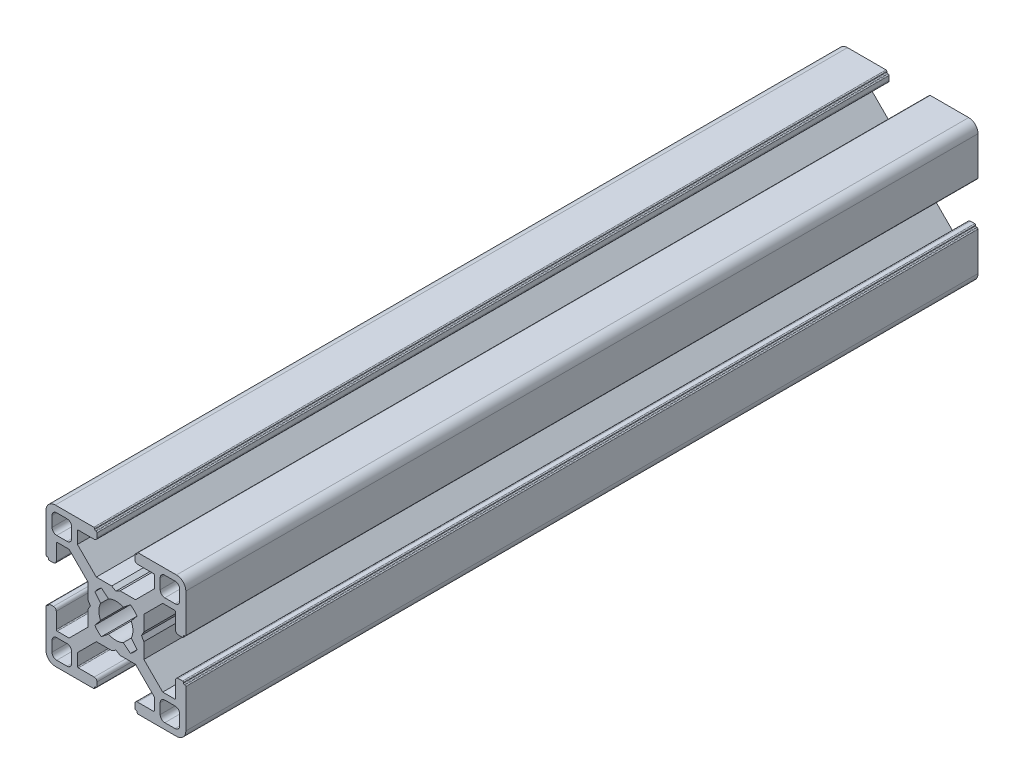
SolidWorks part; units mm, degrees
material "6063 Aluminum Alloy"
ref_plane "Płaszczyzna przednia" through (0, 0, 0) normal (0, 0, 1) x (1, 0, 0)
ref_plane "Płaszczyzna górna" through (0, 0, 0) normal (0, 1, 0) x (1, 0, 0)
ref_plane "Płaszczyzna prawa" through (0, 0, 0) normal (1, 0, 0) x (0, 0, -1)
sketch "Szkic1" plane through (0, 0, 0) normal (0, 0, 1) x (1, 0, 0)
  line L0 (12.7, 13.7) -> (10.5, 13.7)
  line L1 (9.5, 12.7) -> (9.5, 10.5)
  line L2 (10.5, 9.5) -> (12.7, 9.5)
  line L3 (13.7, 10.5) -> (13.7, 12.7)
  line L4 (-1.5829, 3.2889) -> (-3.1172, 4.5314)
  line L5 (-4.5314, 3.1172) -> (-3.2889, 1.5829)
  line L6 (-3.2889, -1.5829) -> (-4.5314, -3.1172)
  line L7 (-3.1172, -4.5314) -> (-1.5829, -3.2889)
  line L8 (1.5829, -3.2889) -> (3.1172, -4.5314)
  line L9 (4.5314, -3.1172) -> (3.2889, -1.5829)
  line L10 (3.2889, 1.5829) -> (4.5314, 3.1172)
  line L11 (3.1172, 4.5314) -> (1.5829, 3.2889)
  line L12 (-12.7, -13.7) -> (-10.5, -13.7)
  line L13 (-9.5, -12.7) -> (-9.5, -10.5)
  line L14 (-10.5, -9.5) -> (-12.7, -9.5)
  line L15 (-13.7, -10.5) -> (-13.7, -12.7)
  line L16 (13.7, -12.7) -> (13.7, -10.5)
  line L17 (12.7, -9.5) -> (10.5, -9.5)
  line L18 (9.5, -10.5) -> (9.5, -12.7)
  line L19 (-10.5, 13.7) -> (-12.7, 13.7)
  line L20 (-13.7, 12.7) -> (-13.7, 10.5)
  line L21 (-12.7, 9.5) -> (-10.5, 9.5)
  line L22 (-9.5, 10.5) -> (-9.5, 12.7)
  line L23 (10.5, -13.7) -> (12.7, -13.7)
  line L24 (0, -5.48) -> (0.9007, -6)
  line L25 (0.9007, -6) -> (4.2039, -6)
  line L26 (4.2039, -6) -> (8.25, -10.0461)
  line L27 (8.25, -10.0461) -> (8.25, -12.6)
  line L28 (8.05, -12.8) -> (4.65, -12.8)
  line L29 (4.05, -13.4) -> (4.05, -14.3)
  line L30 (4.25, -14.5) -> (4.35, -14.5)
  line L31 (4.55, -14.7) -> (4.55, -14.8)
  line L32 (4.75, -15) -> (13, -15)
  line L33 (15, -13) -> (15, -4.75)
  line L34 (14.8, -4.55) -> (14.7, -4.55)
  line L35 (14.5, -4.35) -> (14.5, -4.25)
  line L36 (14.3, -4.05) -> (13.4, -4.05)
  line L37 (12.8, -4.65) -> (12.8, -8.05)
  line L38 (12.6, -8.25) -> (10.0461, -8.25)
  line L39 (10.0461, -8.25) -> (6, -4.2039)
  line L40 (6, -4.2039) -> (6, -0.9007)
  line L41 (6, -0.9007) -> (5.48, 0)
  line L42 (5.48, 0) -> (6, 0.9007)
  line L43 (6, 0.9007) -> (6, 4.2039)
  line L44 (6, 4.2039) -> (10.0461, 8.25)
  line L45 (10.0461, 8.25) -> (12.6, 8.25)
  line L46 (12.8, 8.05) -> (12.8, 4.65)
  line L47 (13.4, 4.05) -> (14.3, 4.05)
  line L48 (14.5, 4.25) -> (14.5, 4.35)
  line L49 (14.7, 4.55) -> (14.8, 4.55)
  line L50 (15, 4.75) -> (15, 13)
  line L51 (13, 15) -> (4.75, 15)
  line L52 (4.55, 14.8) -> (4.55, 14.7)
  line L53 (4.35, 14.5) -> (4.25, 14.5)
  line L54 (4.05, 14.3) -> (4.05, 13.4)
  line L55 (4.65, 12.8) -> (8.05, 12.8)
  line L56 (8.25, 12.6) -> (8.25, 10.0461)
  line L57 (8.25, 10.0461) -> (4.2039, 6)
  line L58 (4.2039, 6) -> (0.9007, 6)
  line L59 (0.9007, 6) -> (0, 5.48)
  line L60 (0, 5.48) -> (-0.9007, 6)
  line L61 (-0.9007, 6) -> (-4.2039, 6)
  line L62 (-4.2039, 6) -> (-8.25, 10.0461)
  line L63 (-8.25, 10.0461) -> (-8.25, 12.6)
  line L64 (-8.05, 12.8) -> (-4.65, 12.8)
  line L65 (-4.05, 13.4) -> (-4.05, 14.3)
  line L66 (-4.25, 14.5) -> (-4.35, 14.5)
  line L67 (-4.55, 14.7) -> (-4.55, 14.8)
  line L68 (-4.75, 15) -> (-13, 15)
  line L69 (-15, 13) -> (-15, 4.75)
  line L70 (-14.8, 4.55) -> (-14.7, 4.55)
  line L71 (-14.5, 4.35) -> (-14.5, 4.25)
  line L72 (-14.3, 4.05) -> (-13.4, 4.05)
  line L73 (-12.8, 4.65) -> (-12.8, 8.05)
  line L74 (-12.6, 8.25) -> (-10.0461, 8.25)
  line L75 (-10.0461, 8.25) -> (-6, 4.2039)
  line L76 (-6, 4.2039) -> (-6, 0.9007)
  line L77 (-6, 0.9007) -> (-5.48, 0)
  line L78 (-5.48, 0) -> (-6, -0.9007)
  line L79 (-6, -0.9007) -> (-6, -4.2039)
  line L80 (-6, -4.2039) -> (-10.0461, -8.25)
  line L81 (-10.0461, -8.25) -> (-12.6, -8.25)
  line L82 (-12.8, -8.05) -> (-12.8, -4.65)
  line L83 (-13.4, -4.05) -> (-14.3, -4.05)
  line L84 (-14.5, -4.25) -> (-14.5, -4.35)
  line L85 (-14.7, -4.55) -> (-14.8, -4.55)
  line L86 (-15, -4.75) -> (-15, -13)
  line L87 (-13, -15) -> (-4.75, -15)
  line L88 (-4.55, -14.8) -> (-4.55, -14.7)
  line L89 (-4.35, -14.5) -> (-4.25, -14.5)
  line L90 (-4.05, -14.3) -> (-4.05, -13.4)
  line L91 (-4.65, -12.8) -> (-8.05, -12.8)
  line L92 (-8.25, -12.6) -> (-8.25, -10.0461)
  line L93 (-8.25, -10.0461) -> (-4.2039, -6)
  line L94 (-4.2039, -6) -> (-0.9007, -6)
  line L95 (-0.9007, -6) -> (0, -5.48)
  line L96 (-3.8891, -3.8891) -> (3.8891, 3.8891) construction
  line L97 (-3.8891, 3.8891) -> (3.8891, -3.8891) construction
  line L98 (55, 0) -> (-55, 0) construction
  arc A0 (10.5, 13.7) -> (9.5, 12.7) centre (10.5, 12.7) ccw
  arc A1 (9.5, 10.5) -> (10.5, 9.5) centre (10.5, 10.5) ccw
  arc A2 (12.7, 9.5) -> (13.7, 10.5) centre (12.7, 10.5) ccw
  arc A3 (13.7, 12.7) -> (12.7, 13.7) centre (12.7, 12.7) ccw
  arc A4 (-3.1172, 4.5314) -> (-4.5314, 3.1172) centre (0, 0) ccw
  arc A5 (-3.2889, 1.5829) -> (-3.2889, -1.5829) centre (0, 0) ccw
  arc A6 (-4.5314, -3.1172) -> (-3.1172, -4.5314) centre (0, 0) ccw
  arc A7 (-1.5829, -3.2889) -> (1.5829, -3.2889) centre (0, 0) ccw
  arc A8 (3.1172, -4.5314) -> (4.5314, -3.1172) centre (0, 0) ccw
  arc A9 (3.2889, -1.5829) -> (3.2889, 1.5829) centre (0, 0) ccw
  arc A10 (4.5314, 3.1172) -> (3.1172, 4.5314) centre (0, 0) ccw
  arc A11 (1.5829, 3.2889) -> (-1.5829, 3.2889) centre (0, 0) ccw
  arc A12 (-10.5, -13.7) -> (-9.5, -12.7) centre (-10.5, -12.7) ccw
  arc A13 (-9.5, -10.5) -> (-10.5, -9.5) centre (-10.5, -10.5) ccw
  arc A14 (-12.7, -9.5) -> (-13.7, -10.5) centre (-12.7, -10.5) ccw
  arc A15 (-13.7, -12.7) -> (-12.7, -13.7) centre (-12.7, -12.7) ccw
  arc A16 (12.7, -13.7) -> (13.7, -12.7) centre (12.7, -12.7) ccw
  arc A17 (13.7, -10.5) -> (12.7, -9.5) centre (12.7, -10.5) ccw
  arc A18 (10.5, -9.5) -> (9.5, -10.5) centre (10.5, -10.5) ccw
  arc A19 (9.5, -12.7) -> (10.5, -13.7) centre (10.5, -12.7) ccw
  arc A20 (-12.7, 13.7) -> (-13.7, 12.7) centre (-12.7, 12.7) ccw
  arc A21 (-13.7, 10.5) -> (-12.7, 9.5) centre (-12.7, 10.5) ccw
  arc A22 (-10.5, 9.5) -> (-9.5, 10.5) centre (-10.5, 10.5) ccw
  arc A23 (-9.5, 12.7) -> (-10.5, 13.7) centre (-10.5, 12.7) ccw
  arc A24 (8.05, -12.8) -> (8.25, -12.6) centre (8.05, -12.6) ccw
  arc A25 (4.65, -12.8) -> (4.05, -13.4) centre (4.65, -13.4) ccw
  arc A26 (4.05, -14.3) -> (4.25, -14.5) centre (4.25, -14.3) ccw
  arc A27 (4.55, -14.7) -> (4.35, -14.5) centre (4.35, -14.7) ccw
  arc A28 (4.55, -14.8) -> (4.75, -15) centre (4.75, -14.8) ccw
  arc A29 (13, -15) -> (15, -13) centre (13, -13) ccw
  arc A30 (15, -4.75) -> (14.8, -4.55) centre (14.8, -4.75) ccw
  arc A31 (14.5, -4.35) -> (14.7, -4.55) centre (14.7, -4.35) ccw
  arc A32 (14.5, -4.25) -> (14.3, -4.05) centre (14.3, -4.25) ccw
  arc A33 (13.4, -4.05) -> (12.8, -4.65) centre (13.4, -4.65) ccw
  arc A34 (12.6, -8.25) -> (12.8, -8.05) centre (12.6, -8.05) ccw
  arc A35 (12.8, 8.05) -> (12.6, 8.25) centre (12.6, 8.05) ccw
  arc A36 (12.8, 4.65) -> (13.4, 4.05) centre (13.4, 4.65) ccw
  arc A37 (14.3, 4.05) -> (14.5, 4.25) centre (14.3, 4.25) ccw
  arc A38 (14.7, 4.55) -> (14.5, 4.35) centre (14.7, 4.35) ccw
  arc A39 (14.8, 4.55) -> (15, 4.75) centre (14.8, 4.75) ccw
  arc A40 (15, 13) -> (13, 15) centre (13, 13) ccw
  arc A41 (4.75, 15) -> (4.55, 14.8) centre (4.75, 14.8) ccw
  arc A42 (4.35, 14.5) -> (4.55, 14.7) centre (4.35, 14.7) ccw
  arc A43 (4.25, 14.5) -> (4.05, 14.3) centre (4.25, 14.3) ccw
  arc A44 (4.05, 13.4) -> (4.65, 12.8) centre (4.65, 13.4) ccw
  arc A45 (8.25, 12.6) -> (8.05, 12.8) centre (8.05, 12.6) ccw
  arc A46 (-8.05, 12.8) -> (-8.25, 12.6) centre (-8.05, 12.6) ccw
  arc A47 (-4.65, 12.8) -> (-4.05, 13.4) centre (-4.65, 13.4) ccw
  arc A48 (-4.05, 14.3) -> (-4.25, 14.5) centre (-4.25, 14.3) ccw
  arc A49 (-4.55, 14.7) -> (-4.35, 14.5) centre (-4.35, 14.7) ccw
  arc A50 (-4.55, 14.8) -> (-4.75, 15) centre (-4.75, 14.8) ccw
  arc A51 (-13, 15) -> (-15, 13) centre (-13, 13) ccw
  arc A52 (-15, 4.75) -> (-14.8, 4.55) centre (-14.8, 4.75) ccw
  arc A53 (-14.5, 4.35) -> (-14.7, 4.55) centre (-14.7, 4.35) ccw
  arc A54 (-14.5, 4.25) -> (-14.3, 4.05) centre (-14.3, 4.25) ccw
  arc A55 (-13.4, 4.05) -> (-12.8, 4.65) centre (-13.4, 4.65) ccw
  arc A56 (-12.6, 8.25) -> (-12.8, 8.05) centre (-12.6, 8.05) ccw
  arc A57 (-12.8, -8.05) -> (-12.6, -8.25) centre (-12.6, -8.05) ccw
  arc A58 (-12.8, -4.65) -> (-13.4, -4.05) centre (-13.4, -4.65) ccw
  arc A59 (-14.3, -4.05) -> (-14.5, -4.25) centre (-14.3, -4.25) ccw
  arc A60 (-14.7, -4.55) -> (-14.5, -4.35) centre (-14.7, -4.35) ccw
  arc A61 (-14.8, -4.55) -> (-15, -4.75) centre (-14.8, -4.75) ccw
  arc A62 (-15, -13) -> (-13, -15) centre (-13, -13) ccw
  arc A63 (-4.75, -15) -> (-4.55, -14.8) centre (-4.75, -14.8) ccw
  arc A64 (-4.35, -14.5) -> (-4.55, -14.7) centre (-4.35, -14.7) ccw
  arc A65 (-4.25, -14.5) -> (-4.05, -14.3) centre (-4.25, -14.3) ccw
  arc A66 (-4.05, -13.4) -> (-4.65, -12.8) centre (-4.65, -13.4) ccw
  arc A67 (-8.25, -12.6) -> (-8.05, -12.8) centre (-8.05, -12.6) ccw
  dimension "D1" = 3.65
  dimension "D7" = 2
  dimension "D9" = 3.65
  dimension "D10" = 5.5
  dimension "D23" = 1
  dimension "D37" = 0.2
  dimension "D59" = 0.6
  dimension "D60" = 0.2
  dimension "D63" = 0.2
  dimension "D64" = 0.2
  dimension "D67" = 0.2
  dimension "D68" = 0.2
  dimension "D69" = 0.2
  dimension "D73" = 0.2
  dimension "D75" = 0.2
  dimension "D76" = 0.2
  dimension "D2" = 30
  dimension "D3" = 30
  dimension "D4" = 8.1
  dimension "D5" = 15
  dimension "D6" = 15
  dimension "D8" = 4.05
  dimension "D11" = 45
  dimension "D12" = 6
  dimension "D13" = 2
  dimension "D14" = 12
  dimension "D15" = 6
  dimension "D16" = 12
  dimension "D17" = 6
  dimension "D18" = 12
  dimension "D19" = 6
  dimension "D20" = 12
  dimension "D21" = 1.3
  dimension "D22" = 1.3
  dimension "D24" = 1.3
  dimension "D25" = 4.2
  dimension "D26" = 4.2
  dimension "D27" = 4.2
  dimension "D28" = 1.3
  dimension "D29" = 4.2
  dimension "D30" = 16.5
  dimension "D31" = 8.25
  dimension "D32" = 2.54
  dimension "D33" = 1.27
  dimension "D34" = 2.54
  dimension "D35" = 1.27
  dimension "D36" = 2.2
  dimension "D38" = 2.2
  dimension "D39" = 2.2
  dimension "D40" = 6
  dimension "D41" = 6
  dimension "D42" = 12
  dimension "D43" = 2
  dimension "D44" = 2
  dimension "D45" = 2
  dimension "D46" = 2.2
  dimension "D47" = 16.5
  dimension "D48" = 8.25
  dimension "D49" = 6
  dimension "D50" = 8.1
  dimension "D51" = 4.05
  dimension "D52" = 0.52
  dimension "D53" = 120
  dimension "D54" = 60
  dimension "D55" = 0.52
  dimension "D56" = 0.52
  dimension "D57" = 0.52
  dimension "D58" = 120
  dimension "D61" = 0.5
  dimension "D62" = 0.5
  dimension "D65" = 0.5
  dimension "D66" = 0.5
  dimension "D70" = 0.5
  dimension "D71" = 0.5
  dimension "D72" = 0.5
  dimension "D74" = 0.5
extrude "Dodanie-wyciągnięcie1" add sketch "Szkic1" along normal mid plane 170
equation "\"D5@Szkic1\"=\"D2@Szkic1\"/2"
equation "\"D6@Szkic1\"=\"D3@Szkic1\"/2"
equation "\"D8@Szkic1\"=\"D4@Szkic1\"/2"
equation "\"D14@Szkic1\"=\"D12@Szkic1\"*2"
equation "\"D15@Szkic1\"=\"D12@Szkic1\""
equation "\"D17@Szkic1\"=\"D12@Szkic1\""
equation "\"D19@Szkic1\"=\"D12@Szkic1\""
equation "\"D31@Szkic1\"=\"D30@Szkic1\"/2"
equation "\"D33@Szkic1\"=\"D32@Szkic1\"/2"
equation "\"D35@Szkic1\"=\"D34@Szkic1\"/2"
equation "\"D42@Szkic1\"=\"D40@Szkic1\"*2"
equation "\"D46@Szkic1\"=\"D36@Szkic1\""
equation "\"D47@Szkic1\"=\"D30@Szkic1\""
equation "\"D48@Szkic1\"=\"D31@Szkic1\""
equation "\"D51@Szkic1\"=\"D50@Szkic1\"/2"
equation "\"D54@Szkic1\"=\"D53@Szkic1\"/2"
equation "\"D55@Szkic1\"=\"D52@Szkic1\""
equation "\"D56@Szkic1\"=\"D52@Szkic1\""
equation "\"D57@Szkic1\"=\"D52@Szkic1\""
